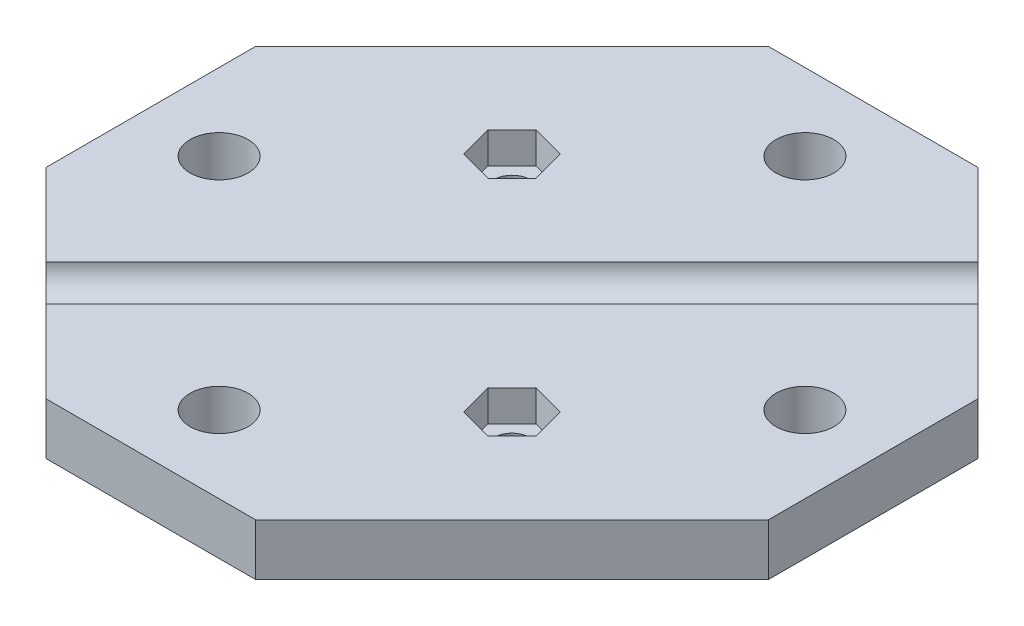
SolidWorks part; units mm, degrees
ref_plane "Front Plane" through (0, 0, 0) normal (0, 0, 1) x (1, 0, 0)
ref_plane "Top Plane" through (0, 0, 0) normal (0, 1, 0) x (1, 0, 0)
ref_plane "Right Plane" through (0, 0, 0) normal (1, 0, 0) x (0, 0, -1)
sketch "Sketch1" plane through (0, 0, 0) normal (0, 1, 0) x (1, 0, 0)
  line L0 (-40.3039, 15.5552) -> (-15.5552, 40.3039)
  line L1 (-40.3039, -40.3039) -> (40.3039, -40.3039) construction
  line L2 (-40.3039, -40.3039) -> (-40.3039, 40.3039) construction
  line L3 (-40.3039, 40.3039) -> (40.3039, 40.3039) construction
  line L4 (40.3039, -40.3039) -> (40.3039, 40.3039) construction
  line L5 (-40.3039, -40.3039) -> (40.3039, 40.3039) construction
  line L6 (-40.3039, 40.3039) -> (40.3039, -40.3039) construction
  line L7 (-27.9296, 27.9296) -> (2.476, -2.476) construction
  line L8 (-11.6661, -16.6182) -> (16.6182, 11.6661) construction
  line L9 (-11.6661, -16.6182) -> (-32.8793, 4.5951) construction
  line L10 (16.6182, 11.6661) -> (-4.5951, 32.8793) construction
  line L11 (-40.3039, 15.5552) -> (-40.3039, -4.6948)
  line L12 (-15.5552, 40.3039) -> (4.6948, 40.3039)
  line L13 (24.0428, 0.706) -> (24.0428, 20.956)
  line L14 (-0.706, -24.0428) -> (-20.956, -24.0428)
  line L15 (-32.8793, 4.5951) -> (-4.5951, 32.8793) construction
  line L16 (-18.7372, 18.7372) -> (11.6684, -11.6684) construction
  line L17 (-0.706, -24.0428) -> (24.0428, 0.706)
  line L18 (-40.3039, -4.6948) -> (-20.956, -24.0428)
  line L19 (4.6948, 40.3039) -> (24.0428, 20.956)
  circle A0 centre (-11.6661, -16.6182) radius 2.8
  circle A1 centre (16.6182, 11.6661) radius 2.8
  circle A2 centre (-4.5951, 32.8793) radius 2.8
  circle A3 centre (-32.8793, 4.5951) radius 2.8
  point P0 (0, 0)
  point P13 (2.476, -2.476)
  point P28 (11.6684, -11.6684)
  dimension "D6" = 5.6
  dimension "D1" = 135
  dimension "D2" = 35
  dimension "D3" = 43
  dimension "D4" = 40
  dimension "D5" = 30
  dimension "D7" = 20.25
  dimension "D8" = 20.25
  dimension "D9" = 43
  dimension "D10" = 35
  dimension "D11" = 20.25
  dimension "D12" = 20.25
extrude "Boss-Extrude1" add sketch "Sketch1" along normal blind 5
sketch "Sketch2" plane through (0, 5, 0) normal (0, 1, 0) x (1, 0, 0)
  line L0 (-27.9296, 27.9296) -> (11.6684, -11.6684) construction
  line L1 (-15.5552, 40.3039) -> (-40.3039, 15.5552) construction
  line L2 (-0.706, -24.0428) -> (24.0428, 0.706) construction
  line L3 (-18.7372, -2.476) -> (2.476, 18.7372) construction
  line L4 (-12.55, 33.7632) -> (17.502, 3.7112) construction
  line L5 (-12.55, 33.7632) -> (-33.7632, 12.55) construction
  line L6 (-33.7632, 12.55) -> (-3.7112, -17.502) construction
  line L7 (-3.7112, -17.502) -> (17.502, 3.7112) construction
  line L8 (15.7343, 5.4789) -> (13.9665, 3.7112) construction
  line L9 (13.9665, 3.7112) -> (15.7343, 1.9434) construction
  line L10 (-5.4789, -15.7343) -> (-3.7112, -13.9665) construction
  line L11 (-3.7112, -13.9665) -> (-1.9434, -15.7343) construction
  line L12 (-23.1566, 23.1566) -> (-21.3181, 21.3181) construction
  circle A0 centre (13.9665, 3.7112) radius 1.75
  circle A1 centre (-3.7112, -13.9665) radius 1.75
  circle A3 centre (-21.3181, 21.3181) radius 1.75
  point P9 (-8.1306, 8.1306)
  point P12 (2.476, 18.7372)
  dimension "D7" = 3.5
  dimension "D10" = 3.5
  dimension "D11" = 2.6
  dimension "D12" = 3.5
  dimension "D1" = 30
  dimension "D2" = 42.5
  dimension "D3" = 30
  dimension "D4" = 42.5
  dimension "D5" = 2.5
  dimension "D6" = 2.5
  dimension "D8" = 2.5
  dimension "D9" = 2.5
sketch "Sketch3" plane through (0, 5, 0) normal (0, 1, 0) x (1, 0, 0)
  line L0 (-30.63, -14.3688) -> (14.3688, 30.63) construction
  line L1 (-40.3039, -4.6948) -> (-20.956, -24.0428) construction
  line L2 (24.0428, 20.956) -> (4.6948, 40.3039) construction
  point P6 (0, 0)
sketch "Sketch4" plane through (22.4994, 0, -22.4994) normal (0.7071, 0, -0.7071) x (-0.7071, 0, -0.7071)
  line L0 (13.9984, 5) -> (8.9984, 5)
  line L1 (-2.1827, 5) -> (25.1795, 5) construction
  arc A0 (8.9984, 5) -> (13.9984, 5) centre (11.4984, 5) ccw
  point P5 (11.4984, 5)
  dimension "D1" = 5
extrude "Cut-Extrude1" cut sketch "Sketch4" against normal up to next
sketch "Sketch5" plane through (0, 5, 0) normal (0, 1, 0) x (1, 0, 0)
  line L0 (11.6684, -11.6684) -> (-6.3628, 6.3628) construction
  line L1 (-0.706, -24.0428) -> (24.0428, 0.706) construction
  line L2 (-28.8622, -16.1366) -> (16.1366, 28.8622) construction
  line L3 (-9.8984, 9.8984) -> (-27.9296, 27.9296) construction
  line L4 (-32.3977, -12.601) -> (12.601, 32.3977) construction
  line L5 (-15.5552, 40.3039) -> (-40.3039, 15.5552) construction
  line L7 (-16.5869, 21.241) -> (-19.7657, 22.0927)
  line L8 (-19.7657, 22.0927) -> (-22.0927, 19.7657)
  line L9 (-22.0927, 19.7657) -> (-21.241, 16.5869)
  line L10 (-21.241, 16.5869) -> (-18.0622, 15.7352)
  line L11 (-18.0622, 15.7352) -> (-15.7352, 18.0622)
  line L12 (-15.7352, 18.0622) -> (-16.5869, 21.241)
  line L13 (4.9798, -0.3258) -> (1.801, 0.526)
  line L14 (1.801, 0.526) -> (-0.526, -1.801)
  line L15 (-0.526, -1.801) -> (0.3258, -4.9798)
  line L16 (0.3258, -4.9798) -> (3.5045, -5.8316)
  line L17 (3.5045, -5.8316) -> (5.8316, -3.5045)
  line L18 (5.8316, -3.5045) -> (4.9798, -0.3258)
  circle A0 centre (-18.914, 18.914) radius 2.85 construction
  circle A1 centre (2.6528, -2.6528) radius 2.85 construction
  dimension "D1" = 5.7
  dimension "D2" = 5.7
extrude "Cut-Extrude2" cut sketch "Sketch5" against normal blind 3
sketch "Sketch6" plane through (0, 5, 0) normal (0, 1, 0) x (1, 0, 0)
  line L0 (-9.8984, 9.8984) -> (-27.9296, 27.9296) construction
  line L1 (-32.3977, -12.601) -> (12.601, 32.3977) construction
  line L2 (-15.5552, 40.3039) -> (-40.3039, 15.5552) construction
  line L3 (-6.3628, 6.3628) -> (11.6684, -11.6684) construction
  line L4 (-28.8622, -16.1366) -> (16.1366, 28.8622) construction
  line L5 (-0.706, -24.0428) -> (24.0428, 0.706) construction
  circle A0 centre (-18.914, 18.914) radius 1.75
  circle A1 centre (2.6528, -2.6528) radius 1.75
  dimension "D1" = 3.5
extrude "Cut-Extrude3" cut sketch "Sketch6" against normal up to next
